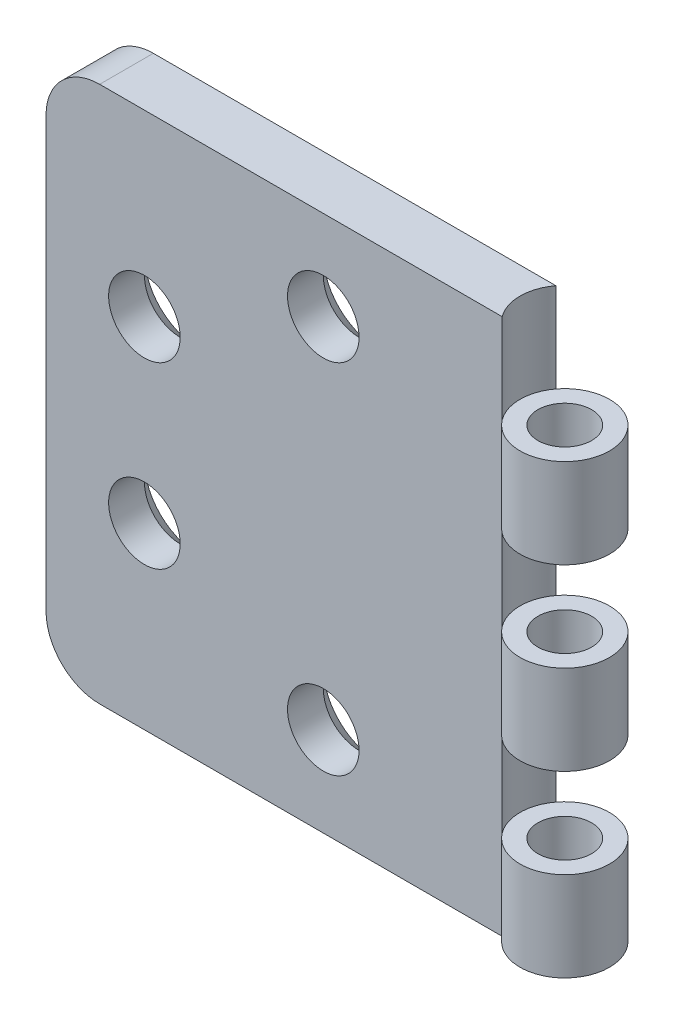
SolidWorks part; units mm, degrees
ref_plane "Спереди" through (0, 0, 0) normal (0, 0, 1) x (1, 0, 0)
ref_plane "Сверху" through (0, 0, 0) normal (0, 1, 0) x (1, 0, 0)
ref_plane "Справа" through (0, 0, 0) normal (1, 0, 0) x (0, 0, -1)
sketch "Эскиз1" plane through (0, 0, 0) normal (0, 0, 1) x (1, 0, 0)
  line L1 (-15, 15) -> (15, 15)
  line L2 (-15, 15) -> (-15, -15)
  line L3 (-15, -15) -> (15, -15)
  line L4 (15, 15) -> (15, -15)
  line L5 (-15, 15) -> (15, -15) construction
  line L6 (-15, -15) -> (15, 15) construction
  point P0 (0, 0)
  dimension "D1" = 30
  dimension "D2" = 30
extrude "Бобышка-Вытянуть1" add sketch "Эскиз1" along normal blind 3
sketch "Эскиз2" plane through (0, -15, 0) normal (0, -1, 0) x (1, 0, 0)
  line L0 (15, 1.5) -> (12.5, 1.5)
  line L1 (15, 3) -> (15, 0) construction
  line L2 (15, 1.5) -> (15, 3)
  line L3 (15, 3) -> (9.5, 3)
  line L4 (15, 0) -> (9.5, 0)
  line L7 (15, 0) -> (15, 1.5)
  circle A0 centre (12.5, 1.5) radius 2.5
  line M2 (-15, 0) -> (15, 0)
  line M3 (15, 0) -> (15, 3)
  line M4 (15, 3) -> (-15, 3)
  dimension "D1" = 5
  dimension "D2" = 2.5
extrude "Вырез-Вытянуть1" cut sketch "Эскиз2" against normal through all contours A0 M2 M3 | A0 M3 M4
sketch "Эскиз3" plane through (0, -15, 0) normal (0, -1, 0) x (1, 0, 0)
  circle A0 centre (12.5, 1.5) radius 2.5
extrude "Бобышка-Вытянуть3" add sketch "Эскиз3" against normal up to surface (30 mm away) up to face at (-0.125, 15, 1.5)
fillet "Скругление1" radius 3 2 edges at (-15, 15, 1.5) (-15, -15, 1.5)
sketch "Эскиз4" plane through (0, 0, 3) normal (0, 0, 1) x (1, 0, 0)
  line L0 (10.5, -15) -> (0.5, -15)
  line L1 (-12, -15) -> (10.5, -15) construction
  line L2 (0.5, -15) -> (0.5, 15)
  line L3 (10.5, 15) -> (-12, 15) construction
  line L4 (0.5, 15) -> (-9.5, 15)
  line L5 (-9.5, 15) -> (-9.5, -15)
  line L6 (0.5, 15) -> (0.5, 10)
  line L7 (-9.5, 15) -> (-9.5, 5)
  line L8 (0.5, 0) -> (-9.5, 0)
  circle A0 centre (0.5, 10) radius 2
  circle A1 centre (-9.5, 5) radius 2
  circle A2 centre (-9.5, -5) radius 2
  circle A3 centre (0.5, -10) radius 2
  dimension "D5" = 4
  dimension "D1" = 10
  dimension "D2" = 10
  dimension "D3" = 5
  dimension "D4" = 10
extrude "Вырез-Вытянуть2" cut sketch "Эскиз4" against normal through all contours A2 L5 | A2 L5 | A3 L2 | A3 L2 | L7 A1 L5 | L5 A1 L7 | L2 A0 | L2 A0
ref_plane "Плоскость1" through (0, -10, 0) normal (0, -1, 0) x (-1, 0, 0)
sketch "Эскиз6" plane through (0, -10, 0) normal (0, -1, 0) x (-1, 0, 0)
  circle A0 centre (-12.5, -1.5) radius 2.5
extrude "Вырез-Вытянуть3" cut sketch "Эскиз6" against normal blind 5
ref_plane "Плоскость2" through (0, 0, 0) normal (0, -1, 0) x (-1, 0, 0)
sketch "Эскиз7" plane through (0, 0, 0) normal (0, -1, 0) x (-1, 0, 0)
  circle A0 centre (-12.5, -1.5) radius 2.5
extrude "Вырез-Вытянуть4" cut sketch "Эскиз7" against normal blind 5
sketch "Эскиз8" plane through (0, 15, 0) normal (0, 1, 0) x (1, 0, 0)
  circle A0 centre (12.5, -1.5) radius 2.5
extrude "Вырез-Вытянуть5" cut sketch "Эскиз8" against normal blind 5
sketch "Эскиз9" plane through (0, -15, 0) normal (0, -1, 0) x (1, 0, 0)
  circle A0 centre (12.5, 1.5) radius 1.5
  dimension "D1" = 3
extrude "Вырез-Вытянуть6" cut sketch "Эскиз9" against normal through all
chamfer "Фаска1" distance 1 angle 45 4 edges at (2.5, 10, 0) (-7.5, 5, 0) (-7.5, -5, 0) (2.5, -10, 0)
